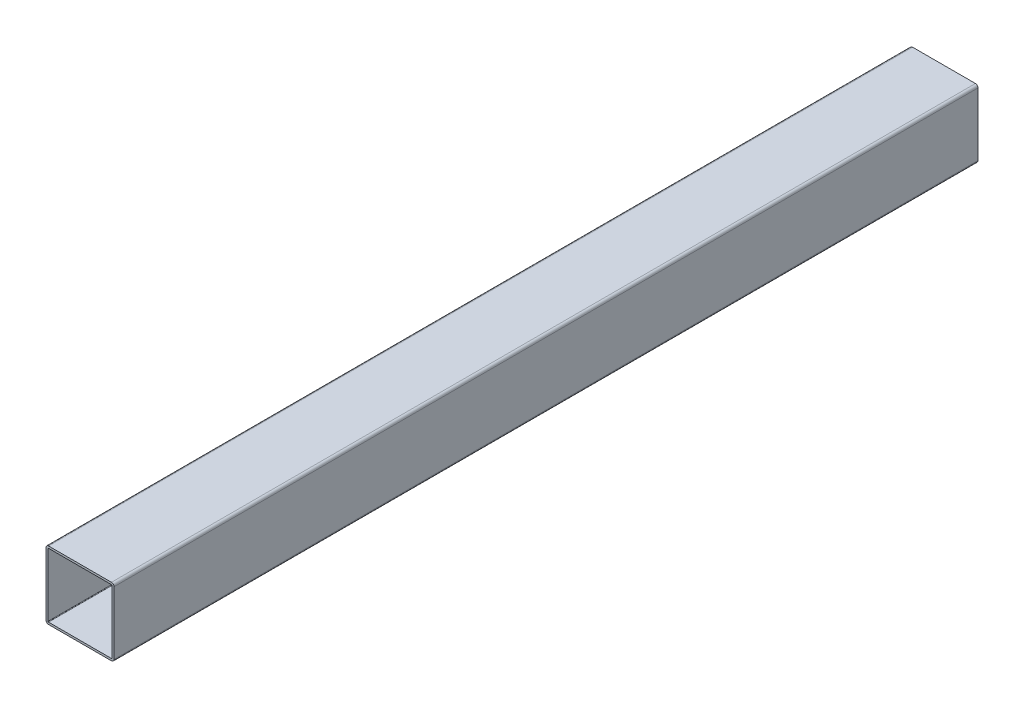
SolidWorks part; units mm, degrees
material "AISI 1020 Steel, Cold Rolled"
ref_plane "Front Plane" through (0, 0, 0) normal (0, 0, 1) x (1, 0, 0)
ref_plane "Top Plane" through (0, 0, 0) normal (0, 1, 0) x (1, 0, 0)
ref_plane "Right Plane" through (0, 0, 0) normal (1, 0, 0) x (0, 0, -1)
sketch "Sketch1" plane through (0, 0, 0) normal (0, 1, 0) x (1, 0, 0)
  line L0 (0, 0) -> (0, 508)
  dimension "D1" = 508
other "Structural Member1"
ref_plane "Plane1" through (0, 0, 0) normal (0, 0, -1) x (-1, 0, 0)
sketch "Sketch12" plane through (0, 0, 0) normal (0, 0, -1) x (-1, 0, 0)
  line L0 (-18.5, -18.8) -> (18.5, -18.8)
  line L1 (-18.8, -18.5) -> (-18.8, 18.5)
  line L2 (18.5, 18.8) -> (-18.5, 18.8)
  line L3 (18.8, 18.5) -> (18.8, -18.5)
  line L4 (-18.5, -20) -> (18.5, -20)
  line L5 (-20, -18.5) -> (-20, 18.5)
  line L6 (18.5, 20) -> (-18.5, 20)
  line L7 (20, 18.5) -> (20, -18.5)
  arc A0 (20, 18.5) -> (18.5, 20) centre (18.5, 18.5) ccw
  arc A1 (18.5, -20) -> (20, -18.5) centre (18.5, -18.5) ccw
  arc A2 (-20, -18.5) -> (-18.5, -20) centre (-18.5, -18.5) ccw
  arc A3 (-18.5, 20) -> (-20, 18.5) centre (-18.5, 18.5) ccw
  arc A4 (-18.5, 18.8) -> (-18.8, 18.5) centre (-18.5, 18.5) ccw
  arc A5 (18.8, 18.5) -> (18.5, 18.8) centre (18.5, 18.5) ccw
  arc A6 (18.5, -18.8) -> (18.8, -18.5) centre (18.5, -18.5) ccw
  arc A7 (-18.8, -18.5) -> (-18.5, -18.8) centre (-18.5, -18.5) ccw
  point P0 (-20, 0)
  point P1 (20, 0)
  point P2 (0, 20)
  point P3 (0, -20)
  point P4 (0, 0)
  point P5 (-20, -20)
  point P6 (20, -20)
  point P7 (20, 20)
  point P8 (-20, 20)
  point P33 (0, 0)
  dimension "D1" = 1.5
  dimension "Thickness" = 1.2
  dimension "V_leg" = 40
